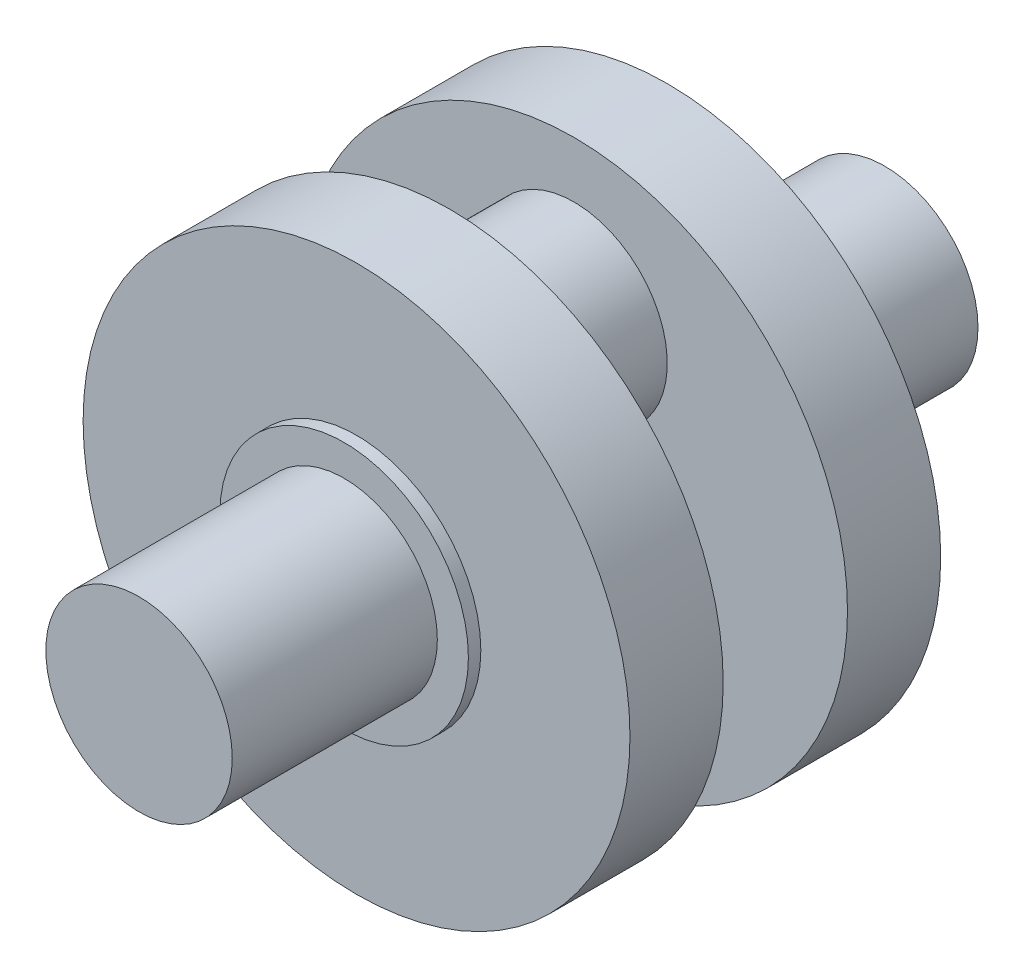
SolidWorks part; units mm, degrees
ref_plane "Płaszczyzna przednia" through (0, 0, 0) normal (0, 0, 1) x (1, 0, 0)
ref_plane "Płaszczyzna górna" through (0, 0, 0) normal (0, 1, 0) x (1, 0, 0)
ref_plane "Płaszczyzna prawa" through (0, 0, 0) normal (1, 0, 0) x (0, 0, -1)
sketch "Szkic1" plane through (0, 0, 0) normal (0, 0, 1) x (1, 0, 0)
  circle A0 centre (0, 0) radius 15
  dimension "D1" = 30
extrude "Dodanie-wyciągnięcie1" add sketch "Szkic1" along normal blind 33 contours A0
sketch "Szkic2" plane through (0, 0, 0) normal (0, 0, 1) x (1, 0, 0)
  circle A0 centre (0, 0) radius 20
  dimension "D1" = 40
extrude "Dodanie-wyciągnięcie2" add sketch "Szkic2" against normal blind 2 contours A0
sketch "Szkic5" plane through (0, 0, -2) normal (0, 0, -1) x (-1, 0, 0)
  circle A0 centre (0, 0) radius 44
  dimension "D1" = 88
extrude "Dodanie-wyciągnięcie5" add sketch "Szkic5" along normal blind 15
sketch "Szkic6" plane through (0, 0, -17) normal (0, 0, -1) x (-1, 0, 0)
  circle A0 centre (0, 20) radius 15
  dimension "D1" = 30
  dimension "D2" = 20
extrude "Dodanie-wyciągnięcie6" add sketch "Szkic6" along normal blind 10 contours A0
mirror "Lustro3" about plane through (0, 20, -27) normal (0, 0, -1) of bodies 108
